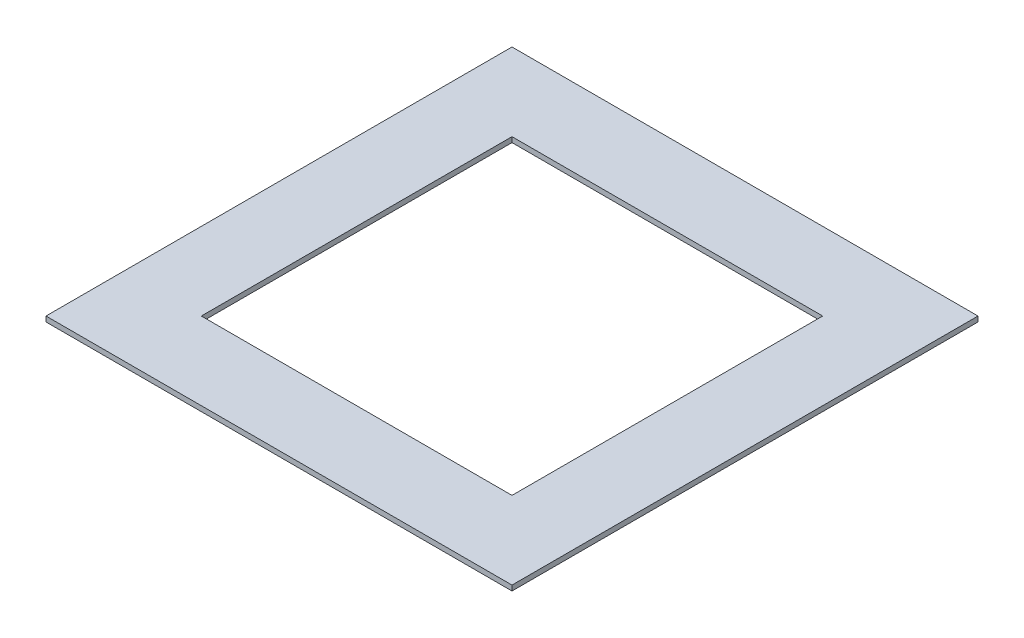
SolidWorks part; units mm, degrees
ref_plane "Alzado" through (0, 0, 0) normal (0, 0, 1) x (1, 0, 0)
ref_plane "Planta" through (0, 0, 0) normal (0, 1, 0) x (1, 0, 0)
ref_plane "Vista lateral" through (0, 0, 0) normal (1, 0, 0) x (0, 0, -1)
sketch "Croquis1" plane through (0, 0, 0) normal (0, 1, 0) x (1, 0, 0)
  line L0 (0, 0) -> (45, 45) construction
  line L1 (0, 0) -> (45, 0)
  line L2 (0, 0) -> (0, 45)
  line L3 (0, 45) -> (45, 45)
  line L4 (45, 0) -> (45, 45)
  line L6 (7.5, 7.5) -> (37.5, 7.5)
  line L7 (7.5, 7.5) -> (7.5, 37.5)
  line L8 (7.5, 37.5) -> (37.5, 37.5)
  line L9 (37.5, 7.5) -> (37.5, 37.5)
  line L10 (7.5, 7.5) -> (37.5, 37.5) construction
  line L11 (7.5, 37.5) -> (37.5, 7.5) construction
  point P4 (22.5, 22.5)
  dimension "D1" = 45
  dimension "D2" = 30
extrude "Saliente-Extruir1" add sketch "Croquis1" along normal blind 0.5
